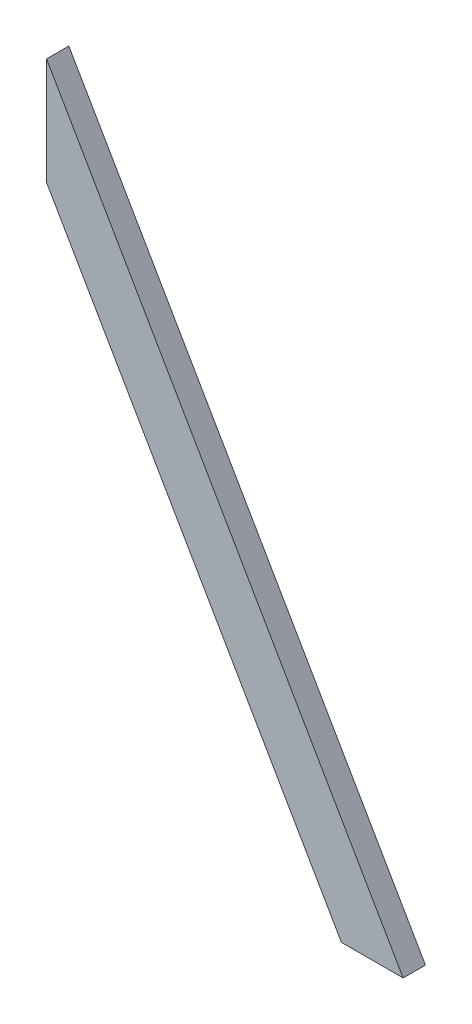
SolidWorks part; units mm, degrees
ref_plane "Plan de face" through (0, 0, 0) normal (0, 0, 1) x (1, 0, 0)
ref_plane "Plan de dessus" through (0, 0, 0) normal (0, 1, 0) x (1, 0, 0)
ref_plane "Plan de droite" through (0, 0, 0) normal (1, 0, 0) x (0, 0, -1)
sketch "Esquisse1" plane through (0, 0, 0) normal (0, 0, 1) x (1, 0, 0)
  line L0 (0, 0) -> (-330.718, 572.8203)
  line L1 (-330.718, 572.8203) -> (-330.718, 692.8203)
  line L2 (-330.718, 692.8203) -> (69.282, 0)
  line L3 (69.282, 0) -> (0, 0)
  dimension "D1" = 60
  dimension "D2" = 60
  dimension "D3" = 800
extrude "Boss.-Extru.1" add sketch "Esquisse1" along normal blind 25
